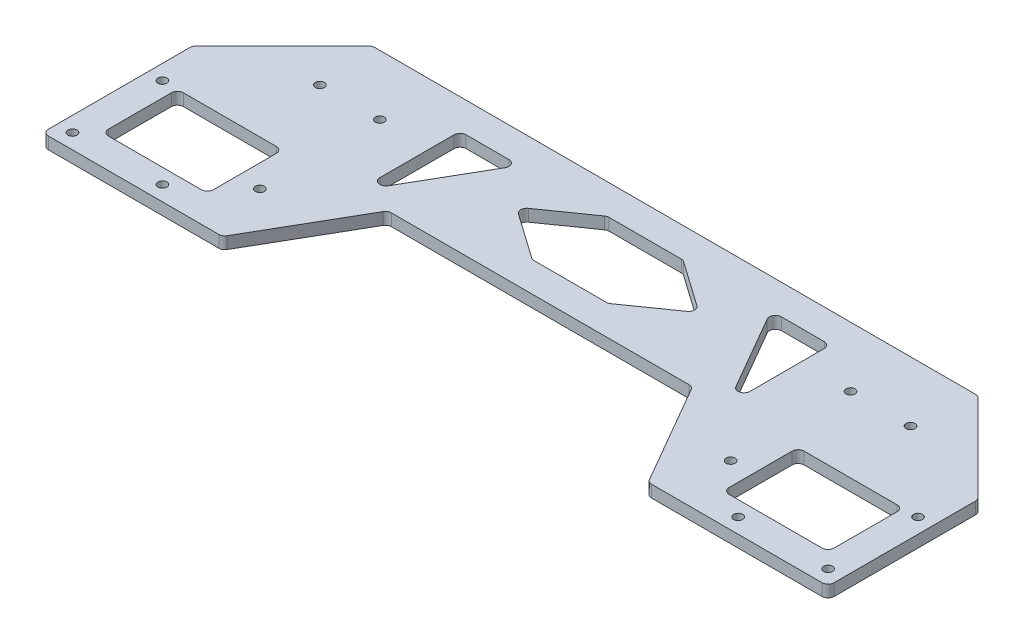
SolidWorks part; units mm, degrees
ref_plane "前视基准面" through (0, 0, 0) normal (0, 0, 1) x (1, 0, 0)
ref_plane "上视基准面" through (0, 0, 0) normal (0, 1, 0) x (1, 0, 0)
ref_plane "右视基准面" through (0, 0, 0) normal (1, 0, 0) x (0, 0, -1)
sketch "草图1" plane through (0, 0, 0) normal (0, 1, 0) x (1, 0, 0)
  line L0 (65.5488, -39.6711) -> (125.5488, -39.6711)
  line L1 (-136.4512, -39.6711) -> (-76.4512, -39.6711)
  line L2 (-136.4512, -39.6711) -> (-136.4512, 10.3289)
  line L3 (-106.4512, 40.3289) -> (95.5488, 40.3289)
  line L4 (125.5488, -39.6711) -> (125.5488, 10.3289)
  line L5 (-76.4512, -39.6711) -> (-56.244, -4.6711)
  line L6 (65.5488, -39.6711) -> (45.3415, -4.6711)
  line L7 (-136.4512, 10.3289) -> (-106.4512, 40.3289)
  line L8 (125.5488, 10.3289) -> (95.5488, 40.3289)
  line L9 (-56.244, -4.6711) -> (45.3415, -4.6711)
  point P0 (0, 0)
  point P6 (0, -48.9713)
  dimension "D1" = 142
  dimension "D2" = 45
  dimension "D3" = 60
  dimension "D4" = 60
  dimension "D5" = 60
  dimension "D6" = 60
  dimension "D7" = 45
  dimension "D8" = 45
  dimension "D9" = 35
  dimension "D10" = 30
  dimension "D11" = 30
extrude "凸台-拉伸1" add sketch "草图1" along normal blind 4
sketch "草图2" plane through (0, 4, 0) normal (0, 1, 0) x (1, 0, 0)
  line L0 (-56.244, -4.6711) -> (45.3415, -4.6711) construction
  line L2 (7.2169, 30.3289) -> (-18.1194, 30.3289)
  line L5 (-18.1194, 5.3289) -> (7.2169, 5.3289)
  line L8 (-18.1194, 30.3289) -> (-35.9025, 17.8289)
  line L9 (-35.9025, 17.8289) -> (-18.1194, 5.3289)
  line L10 (7.2169, 30.3289) -> (25, 17.8289)
  line L11 (25, 17.8289) -> (7.2169, 5.3289)
  line L13 (-7.2169, 30.3289) -> (-10.8253, 24.0789) [skipped]
  line L14 (-16.949, 22.1855) -> (-13.3406, 15.9355) [skipped]
  line L15 (4.7016, 0.9723) -> (8.31, 7.2223) [skipped]
  line L16 (4.7016, 34.6855) -> (1.0932, 40.9355) [skipped]
  point P0 (-5.4512, -4.6711)
  point P2 (-5.4512, 5.3289)
  point P5 (-5.4512, 30.3289)
  dimension "D1" = 0
  dimension "D2" = 10
  dimension "D3" = 0
extrude "切除-拉伸1" cut sketch "草图2" against normal blind 4
sketch "草图3" plane through (0, 4, 0) normal (0, 1, 0) x (1, 0, 0)
  line L0 (-67.1777, 30.3289) -> (-47.4293, 30.3289)
  line L1 (-47.4293, 30.3289) -> (-67.1777, -3.8762)
  line L2 (-67.1777, -3.8762) -> (-67.1777, 30.3289)
  line L3 (95.5488, 40.3289) -> (-106.4512, 40.3289) construction
  line L4 (-76.4512, -39.6711) -> (-56.244, -4.6711) construction
  line L5 (-5.4512, 58.7667) -> (-5.4512, -43.0017) construction
  line L6 (56.2752, -3.8762) -> (56.2752, 30.3289)
  line L7 (56.2752, 30.3289) -> (36.5269, 30.3289)
  line L8 (36.5269, 30.3289) -> (56.2752, -3.8762)
  dimension "D1" = 10
  dimension "D2" = 360
  dimension "D3" = 9.8663
extrude "切除-拉伸2" cut sketch "草图3" against normal blind 4
sketch "草图4" plane through (0, 4, 0) normal (0, 1, 0) x (1, 0, 0)
  line L0 (-136.4512, -39.6711) -> (-76.4512, -39.6711) construction
  line L1 (-124.4512, -29.6711) -> (-93.4512, -29.6711)
  line L2 (-126.4512, -27.6711) -> (-126.4512, -6.6711)
  line L3 (-124.4512, -4.6711) -> (-93.4512, -4.6711)
  line L4 (-91.4512, -27.6711) -> (-91.4512, -6.6711)
  line L5 (-136.4512, 10.3289) -> (-136.4512, -39.6711) construction
  line L6 (-5.4512, 47.6056) -> (-5.4512, -41.5347) construction
  line L7 (115.5488, -27.6711) -> (115.5488, -6.6711)
  line L8 (113.5488, -29.6711) -> (82.5488, -29.6711)
  line L9 (113.5488, -4.6711) -> (82.5488, -4.6711)
  line L10 (80.5488, -27.6711) -> (80.5488, -6.6711)
  arc A0 (-93.4512, -29.6711) -> (-91.4512, -27.6711) centre (-93.4512, -27.6711) ccw
  arc A1 (-124.4512, -29.6711) -> (-126.4512, -27.6711) centre (-124.4512, -27.6711) cw
  arc A2 (-126.4512, -6.6711) -> (-124.4512, -4.6711) centre (-124.4512, -6.6711) cw
  arc A3 (-93.4512, -4.6711) -> (-91.4512, -6.6711) centre (-93.4512, -6.6711) cw
  arc A4 (115.5488, -6.6711) -> (113.5488, -4.6711) centre (113.5488, -6.6711) ccw
  arc A5 (115.5488, -27.6711) -> (113.5488, -29.6711) centre (113.5488, -27.6711) cw
  arc A6 (82.5488, -29.6711) -> (80.5488, -27.6711) centre (82.5488, -27.6711) cw
  arc A7 (82.5488, -4.6711) -> (80.5488, -6.6711) centre (82.5488, -6.6711) ccw
  point P16 (-91.4512, -29.6711)
  point P19 (-126.4512, -29.6711)
  point P22 (-126.4512, -4.6711)
  point P25 (-91.4512, -4.6711)
  point P28 (115.5488, -4.6711)
  point P31 (115.5488, -29.6711)
  point P34 (80.5488, -29.6711)
  point P37 (80.5488, -4.6711)
  dimension "D5" = 2
  dimension "D6" = 2
  dimension "D1" = 35
  dimension "D2" = 10
  dimension "D3" = 10
  dimension "D4" = 25
extrude "切除-拉伸3" cut sketch "草图4" against normal blind 4
fillet "圆角1" radius 2 6 edges at (56.2752, 2, -30.3289) (36.5269, 2, -30.3289) (56.2752, 2, 3.8762) (-67.1777, 2, 3.8762) (-47.4293, 2, -30.3289) (-67.1777, 2, -30.3289)
fillet "圆角2" radius 2 10 edges at (-56.244, 2, 4.6711) (45.3415, 2, 4.6711) (125.5488, 2, -10.3289) (95.5488, 2, -40.3289) (-106.4512, 2, -40.3289) (-136.4512, 2, -10.3289) (125.5488, 2, 39.6711) (65.5488, 2, 39.6711) (-76.4512, 2, 39.6711) (-136.4512, 2, 39.6711)
sketch "草图5" plane through (0, 4, 0) normal (0, 1, 0) x (1, 0, 0)
  line L0 (66.7035, -39.6711) -> (123.5488, -39.6711) construction
  line L1 (125.5488, -37.6711) -> (125.5488, 9.5004) construction
  line L2 (-5.4512, 49.0361) -> (-5.4512, -35.8407) construction
  circle A0 centre (73.0488, -19.6711) radius 1.5
  circle A1 centre (73.0488, 20.3289) radius 1.5
  circle A2 centre (-83.9512, -19.6711) radius 1.5
  circle A3 centre (-83.9512, 20.3289) radius 1.5
  dimension "D1" = 20
  dimension "D2" = 52.5
  dimension "D3" = 40
extrude "切除-拉伸4" cut sketch "草图5" against normal blind 4
sketch "草图6" plane through (0, 4, 0) normal (0, 1, 0) x (1, 0, 0)
  line L0 (66.7035, -39.6711) -> (123.5488, -39.6711) construction
  line L1 (125.5488, -37.6711) -> (125.5488, 9.5004) construction
  circle A0 centre (120.5488, -34.6711) radius 1.5
  circle A1 centre (93.0488, 20.3289) radius 1.5
  circle A2 centre (73.0488, 20.3289) radius 1.5 construction
  circle A3 centre (90.5488, -34.6711) radius 1.5
  dimension "D1" = 5
  dimension "D2" = 5
  dimension "D3" = 20
  dimension "D4" = 30
extrude "切除-拉伸5" cut sketch "草图6" against normal blind 4
sketch "草图7" plane through (0, 4, 0) normal (0, 1, 0) x (1, 0, 0)
  circle A0 centre (120.5488, -4.6711) radius 1.5
  circle A1 centre (120.5488, -34.6711) radius 1.5 construction
  dimension "D1" = 30
extrude "切除-拉伸6" cut sketch "草图7" against normal blind 4
sketch "草图8" plane through (0, 4, 0) normal (0, 1, 0) x (1, 0, 0)
  line L0 (-134.4512, -39.6711) -> (-77.6059, -39.6711) construction
  line L1 (-136.4512, 9.5004) -> (-136.4512, -37.6711) construction
  circle A0 centre (-131.4512, -34.6711) radius 1.5
  circle A1 centre (-101.4512, -34.6711) radius 1.5
  circle A2 centre (-131.4512, -4.6711) radius 1.5
  dimension "D1" = 5
  dimension "D2" = 5
  dimension "D3" = 30
  dimension "D4" = 30
extrude "切除-拉伸7" cut sketch "草图8" against normal blind 4
sketch "草图9" plane through (0, 4, 0) normal (0, 1, 0) x (1, 0, 0)
  circle A0 centre (-103.9512, 20.3289) radius 1.5
  circle A1 centre (-83.9512, 20.3289) radius 1.5 construction
  dimension "D1" = 20
extrude "切除-拉伸8" cut sketch "草图9" against normal blind 4
fillet "圆角3" radius 2 6 edges at (-35.9025, 2, -17.8289) (-18.1194, 2, -5.3289) (7.2169, 2, -5.3289) (25, 2, -17.8289) (7.2169, 2, -30.3289) (-18.1194, 2, -30.3289)
